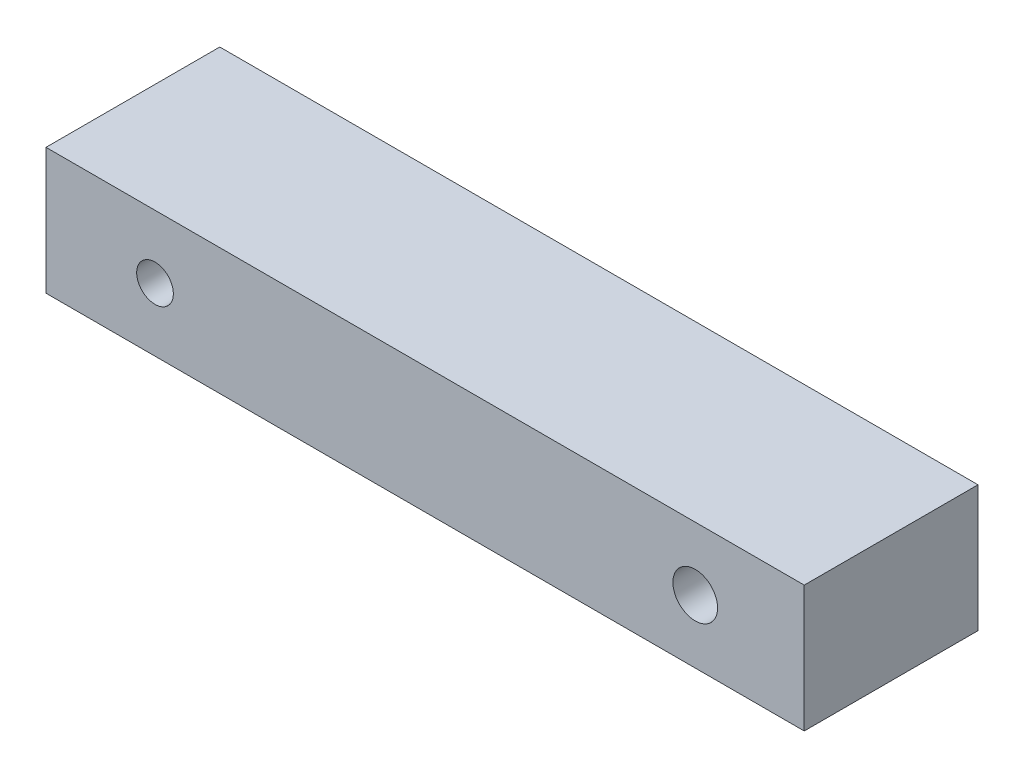
SolidWorks part; units mm, degrees
ref_plane "Front Plane" through (0, 0, 0) normal (0, 0, 1) x (1, 0, 0)
ref_plane "Top Plane" through (0, 0, 0) normal (0, 1, 0) x (1, 0, 0)
ref_plane "Right Plane" through (0, 0, 0) normal (1, 0, 0) x (0, 0, -1)
sketch "Sketch1" plane through (0, 0, 0) normal (1, 0, 0) x (0, 0, -1)
  line L0 (-17.4625, -12.7) -> (-17.4625, 12.7)
  line L1 (-17.4625, -12.7) -> (17.4625, -12.7)
  line L2 (-17.4625, 12.7) -> (17.4625, 12.7)
  line L3 (17.4625, -12.7) -> (17.4625, 12.7)
  line L4 (-17.4625, -12.7) -> (17.4625, 12.7) construction
  line L5 (-17.4625, 12.7) -> (17.4625, -12.7) construction
  point P1 (0, 0)
  dimension "D1" = 34.925
  dimension "D2" = 25.4
extrude "Boss-Extrude1" add sketch "Sketch1" along normal mid plane 152.4
sketch "Sketch2" plane through (0, 0, 17.4625) normal (0, 0, 1) x (1, 0, 0)
  line L0 (-54.291, 0) -> (54.291, 0) construction
  line L1 (76.2, 12.7) -> (-76.2, 12.7) construction
  circle A0 centre (-54.291, 0) radius 3.6875
  circle A1 centre (54.291, 0) radius 4.4911
extrude "Cut-Extrude1" cut sketch "Sketch2" against normal through all
